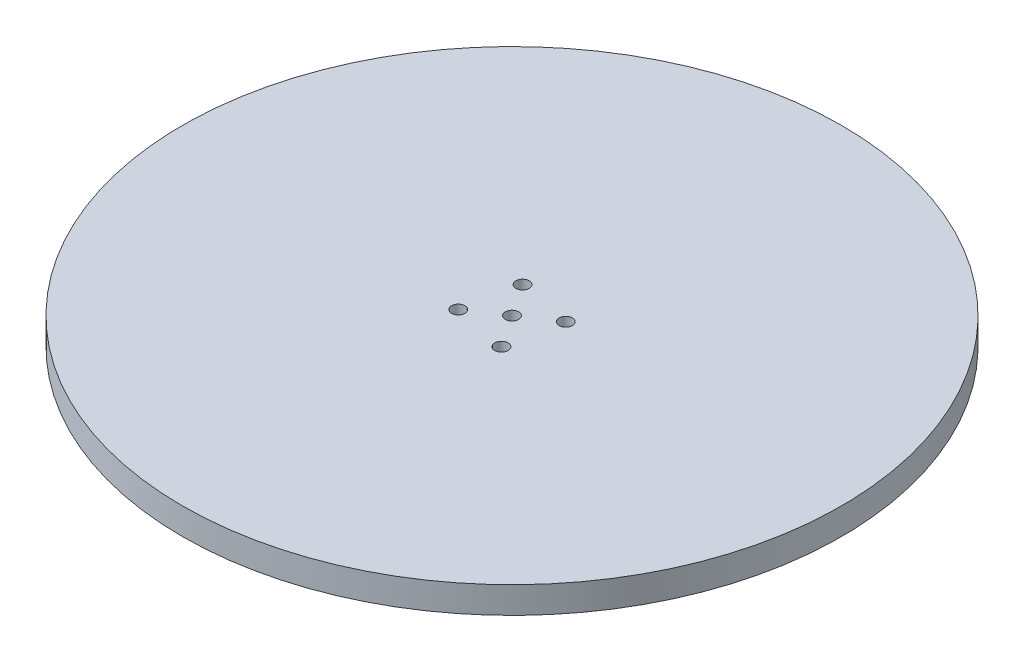
SolidWorks part; units mm, degrees
ref_plane "Front Plane" through (0, 0, 0) normal (0, 0, 1) x (1, 0, 0)
ref_plane "Top Plane" through (0, 0, 0) normal (0, 1, 0) x (1, 0, 0)
ref_plane "Right Plane" through (0, 0, 0) normal (1, 0, 0) x (0, 0, -1)
sketch "Sketch2" plane through (0, 0, 0) normal (0, 1, 0) x (1, 0, 0)
  circle A0 centre (0, 0) radius 61.9125
extrude "Boss-Extrude1" add sketch "Sketch2" along normal blind 5
sketch "Sketch3" plane through (0, 0, 0) normal (0, 1, 0) x (1, 0, 0)
  circle A0 centre (0, 0) radius 23.5
  circle A1 centre (0, 0) radius 32.5
  dimension "D1" = 47
  dimension "D2" = 65
extrude "Boss-Extrude2" add sketch "Sketch3" against normal blind 7
sketch "Sketch6" plane through (0, 0, 0) normal (0, 1, 0) x (1, 0, 0)
  circle A0 centre (0, 0) radius 14.85
extrude "Boss-Extrude3" add sketch "Sketch6" against normal blind 2
sketch "Sketch5" plane through (0, 0, 0) normal (0, -1, 0) x (-1, 0, 0)
  line L0 (0, 0) -> (-4.0585, -6.0438)
  circle A0 centre (0, 0) radius 10
  circle A1 centre (0, 0) radius 1.25
  circle A2 centre (-4.0585, -6.0438) radius 1.25
  circle A3 centre (-6.0438, 4.0585) radius 1.25
  circle A4 centre (4.0585, 6.0438) radius 1.25
  circle A5 centre (6.0438, -4.0585) radius 1.25
  point P15 (0, 0)
  dimension "D1" = 4
extrude "Cut-Extrude1" cut sketch "Sketch5" against normal blind 5 and the other way blind 2 contours A3 | A2 | A5 | A4 | A1
